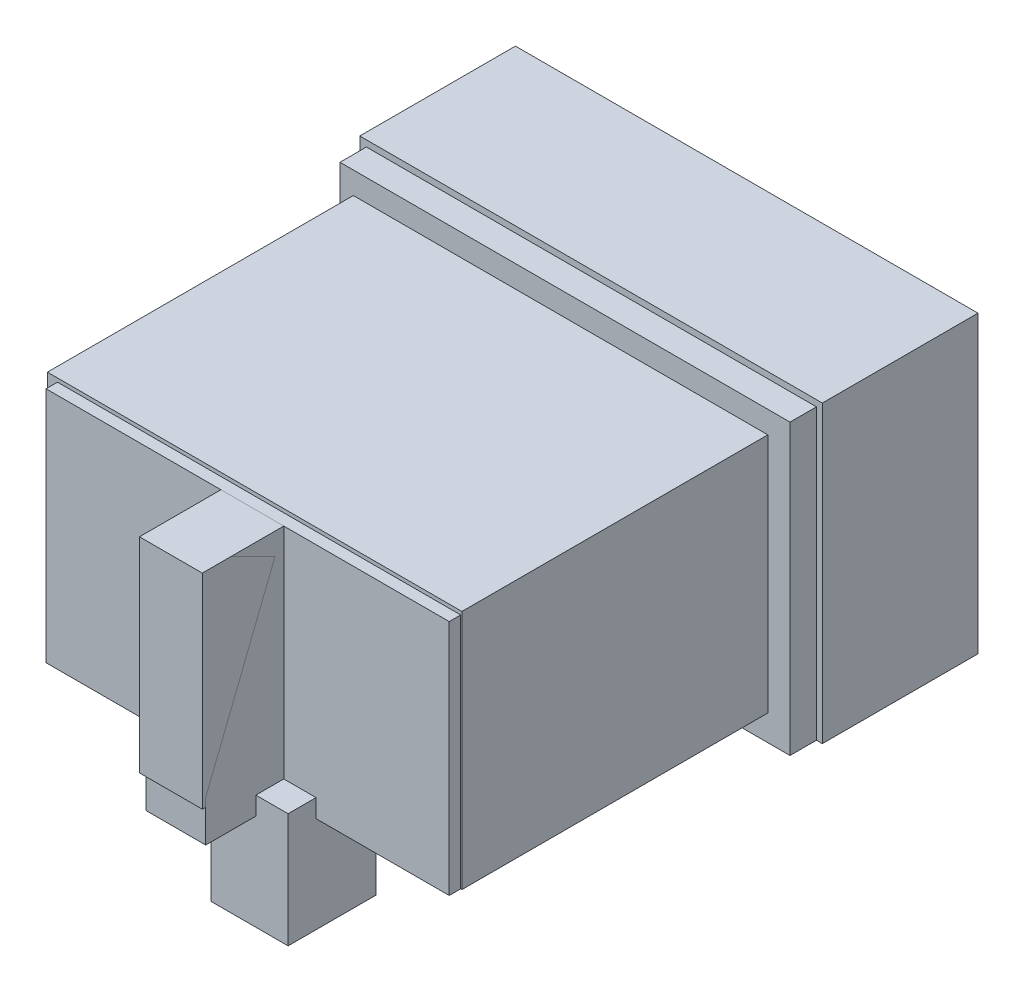
SolidWorks part; units mm, degrees
other "COLL.BOX-Estrusione-Estrusione8"
other "COLL.BOX-Estrusione-Estrusione7"
other "COLL.BOX-Estrusione-Estrusione6"
other "COLL.BOX-Estrusione-Estrusione5"
ref_plane "Piano frontale" through (0, 0, 0) normal (0, 0, 1) x (1, 0, 0)
ref_plane "Piano superiore" through (0, 0, 0) normal (0, 1, 0) x (1, 0, 0)
ref_plane "Piano destro" through (0, 0, 0) normal (1, 0, 0) x (0, 0, -1)
sketch "Schizzo1" plane through (0, 0, 0) normal (0, 0, 1) x (1, 0, 0)
  line L1 (-432.5, 277.5) -> (432.5, 277.5)
  line L2 (-432.5, 277.5) -> (-432.5, -277.5)
  line L3 (-432.5, -277.5) -> (432.5, -277.5)
  line L4 (432.5, 277.5) -> (432.5, -277.5)
  line L5 (-432.5, 277.5) -> (432.5, -277.5) construction
  line L6 (-432.5, -277.5) -> (432.5, 277.5) construction
  point P0 (0, 0)
  dimension "D1" = 555
  dimension "D2" = 865
extrude "Estrusione-Estrusione1" add sketch "Schizzo1" against normal blind 350
sketch "Schizzo2" plane through (0, 0, 0) normal (0, 0, 1) x (1, 0, 0)
  line L1 (-387.5, 228) -> (387.5, 228)
  line L2 (-387.5, 228) -> (-387.5, -228)
  line L3 (-387.5, -228) -> (387.5, -228)
  line L4 (387.5, 228) -> (387.5, -228)
  line L5 (-387.5, 228) -> (387.5, -228) construction
  line L6 (-387.5, -228) -> (387.5, 228) construction
  point P0 (0, 0)
  dimension "D1" = 775
  dimension "D2" = 456
extrude "Estrusione-Estrusione2" add sketch "Schizzo2" along normal blind 610 separate body
sketch "Schizzo3" plane through (0, 0, 610) normal (0, 0, 1) x (1, 0, 0)
  line L0 (-387.5, 228) -> (-387.5, -228) construction
  line L1 (-45.5, 228) -> (69.5, 228)
  line L2 (-45.5, 228) -> (-45.5, -228)
  line L3 (-45.5, -228) -> (69.5, -228)
  line L4 (69.5, 228) -> (69.5, -228)
  line L5 (-45.5, 228) -> (69.5, -228) construction
  line L6 (-45.5, -228) -> (69.5, 228) construction
  line L8 (387.5, 228) -> (-387.5, 228) construction
  line L9 (-387.5, -228) -> (387.5, -228) construction
  point P0 (0, 0)
  dimension "D1" = 342
  dimension "D2" = 115
  dimension "D3" = 0
  dimension "D4" = 0
extrude "Estrusione-Estrusione3" add sketch "Schizzo3" along normal blind 150 separate body
sketch "Schizzo4" plane through (0, -228, 0) normal (0, -1, 0) x (-1, 0, 0)
  line L0 (387.5, -610) -> (387.5, 0) construction
  line L1 (12.5, -660) -> (-127.5, -660)
  line L2 (12.5, -660) -> (12.5, -495)
  line L3 (12.5, -495) -> (-127.5, -495)
  line L4 (-127.5, -660) -> (-127.5, -495)
  line L5 (12.5, -660) -> (-127.5, -495) construction
  line L6 (12.5, -495) -> (-127.5, -660) construction
  line L8 (387.5, 0) -> (-387.5, 0) construction
  point P0 (-57.5, -577.5)
  dimension "D1" = 375
  dimension "D2" = 140
  dimension "D3" = 165
  dimension "D4" = 495
extrude "Estrusione-Estrusione4" add sketch "Schizzo4" along normal blind 185 and the other way blind 30 separate body
sketch "Schizzo5" plane through (0, -277.5, 0) normal (0, -1, 0) x (-1, 0, 0)
  line L1 (445.2132, 50.8033) -> (-443.8075, 50.8033)
  line L2 (445.2132, 50.8033) -> (445.2132, 350)
  line L3 (445.2132, 350) -> (-443.8075, 350)
  line L4 (-443.8075, 50.8033) -> (-443.8075, 350)
  line L5 (432.5, 350) -> (-432.5, 350) construction
  point P4 (0, 0)
  dimension "D1" = 0
extrude "Estrusione-Estrusione5" add sketch "Schizzo5" against normal blind 567 separate body
sketch "Schizzo6" plane through (0, -228, 0) normal (0, -1, 0) x (-1, 0, 0)
  line L1 (406.8347, 0) -> (-389.8462, 0)
  line L2 (406.8347, 0) -> (406.8347, -587.9686)
  line L3 (406.8347, -587.9686) -> (-389.8462, -587.9686)
  line L4 (-389.8462, 0) -> (-389.8462, -587.9686)
extrude "Estrusione-Estrusione6" add sketch "Schizzo6" against normal blind 463 separate body
sketch "Schizzo7" plane through (0, -413, 0) normal (0, -1, 0) x (-1, 0, 0)
  line L1 (16.6351, -495) -> (-131.5048, -495)
  line L2 (16.6351, -495) -> (16.6351, -663.7069)
  line L3 (16.6351, -663.7069) -> (-131.5048, -663.7069)
  line L4 (-131.5048, -495) -> (-131.5048, -663.7069)
extrude "Estrusione-Estrusione7" add sketch "Schizzo7" against normal blind 220 separate body
sketch "Schizzo8" plane through (0, 228, 0) normal (0, 1, 0) x (1, 0, 0)
  line L1 (69.5, -610) -> (-51.287, -610)
  line L2 (69.5, -610) -> (69.5, -766.5836)
  line L3 (69.5, -766.5836) -> (-51.287, -766.5836)
  line L4 (-51.287, -610) -> (-51.287, -766.5836)
extrude "Estrusione-Estrusione8" add sketch "Schizzo8" against normal blind 393 separate body
